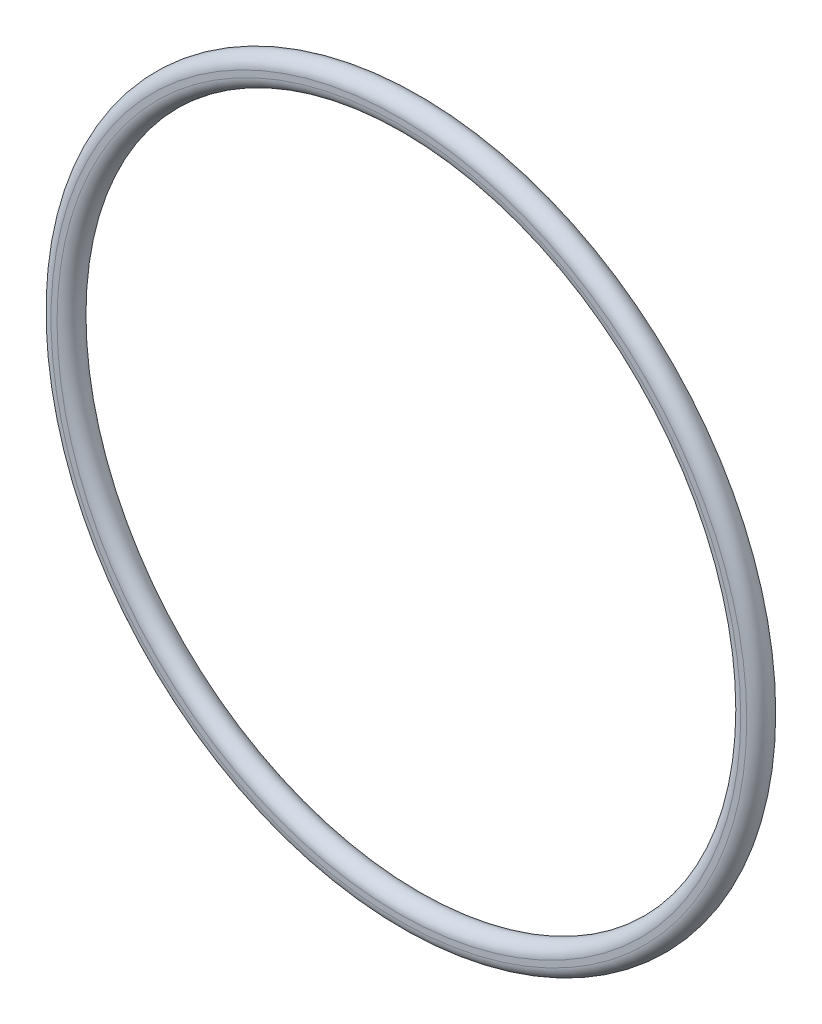
SolidWorks part; units mm, degrees
material "POLYURETHANE (11671)"
ref_plane "Front Plane" through (0, 0, 0) normal (0, 0, 1) x (1, 0, 0)
ref_plane "Top Plane" through (0, 0, 0) normal (0, 1, 0) x (1, 0, 0)
ref_plane "Right Plane" through (0, 0, 0) normal (1, 0, 0) x (0, 0, -1)
sketch "Sketch1" plane through (0, 0, 0) normal (0, 1, 0) x (1, 0, 0)
  line L0 (0, 0) -> (0, 16.7726) construction
  line L1 (23.0188, 0) -> (22.6219, 0) construction
  line L2 (23.0188, -0.7937) -> (22.6219, -0.7938)
  line L3 (23.0188, 0.7937) -> (22.6219, 0.7937)
  circle A1 centre (23.0188, 0) radius 0.7937
  arc A2 (23.0188, -0.7937) -> (23.0188, 0.7937) centre (23.0188, 0) ccw
  arc A3 (22.6219, 0.7937) -> (22.6219, -0.7938) centre (22.6219, 0) ccw
  point P2 (22.8203, 0)
  point P11 (23.0188, 0.7937)
  dimension "D1" = 1.5875
  dimension "D2" = 23.0188
  dimension "D3" = 0.3969
revolve "Revolve1" add sketch "Sketch1" angle 360 about L0
